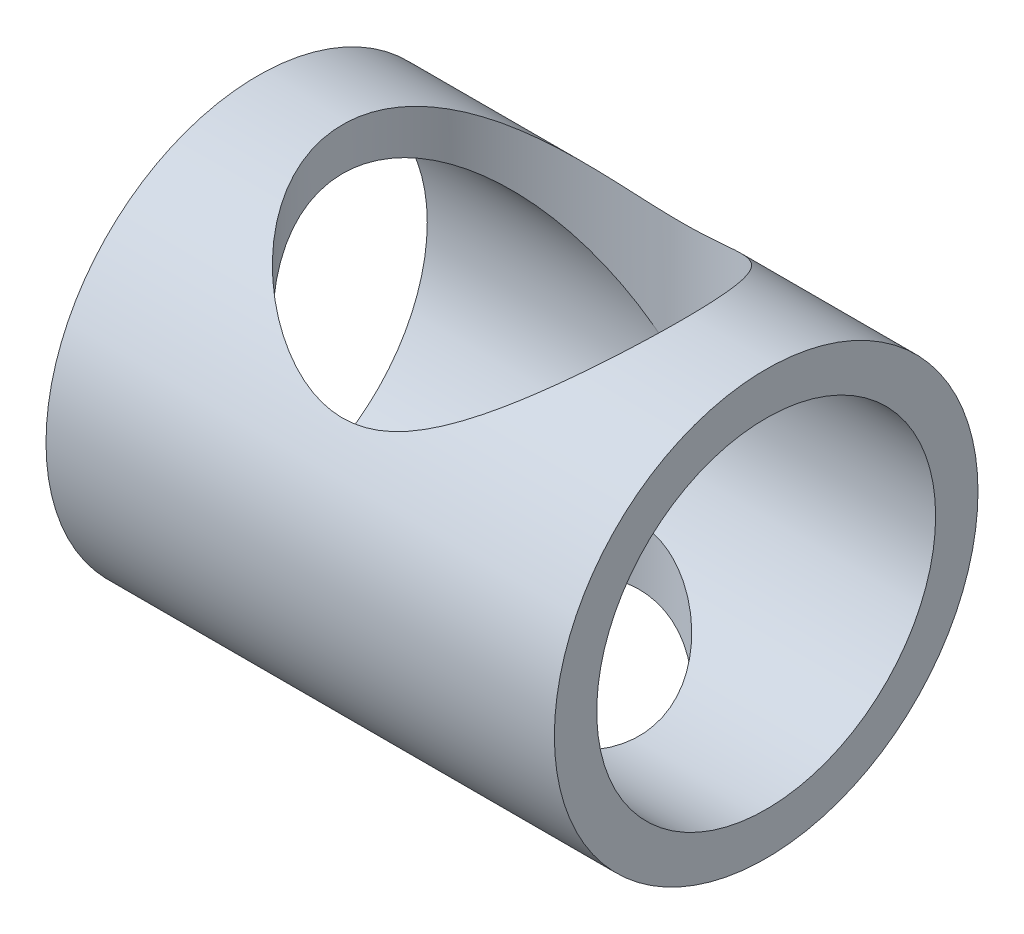
SolidWorks part; units mm, degrees
ref_plane "前视基准面" through (0, 0, 0) normal (0, 0, 1) x (1, 0, 0)
ref_plane "上视基准面" through (0, 0, 0) normal (0, 1, 0) x (1, 0, 0)
ref_plane "右视基准面" through (0, 0, 0) normal (1, 0, 0) x (0, 0, -1)
other "Configuration Table"
sketch "草图1" plane through (0, 0, 0) normal (1, 0, 0) x (0, 0, -1)
  circle A0 centre (0, 0) radius 25
  dimension "D1" = 50
extrude "凸台-拉伸1" add sketch "草图1" along normal mid plane 60
sketch "草图2" plane through (0, 0, 0) normal (1, 0, 0) x (0, 0, -1)
  circle A0 centre (0, 0) radius 20
  dimension "D1" = 40
extrude "切除-拉伸1" cut sketch "草图2" against normal mid plane 60
sketch "草图3" plane through (0, 0, 0) normal (0, 1, 0) x (1, 0, 0)
  circle A0 centre (0, 0) radius 20
  dimension "D1" = 40
extrude "切除-拉伸2" cut sketch "草图3" along normal blind 40
sketch "草图4" plane through (0, 0, 0) normal (0, 1, 0) x (1, 0, 0)
  circle A0 centre (0, 0) radius 15
  dimension "D1" = 30
extrude "切除-拉伸4" cut sketch "草图4" against normal blind 200
